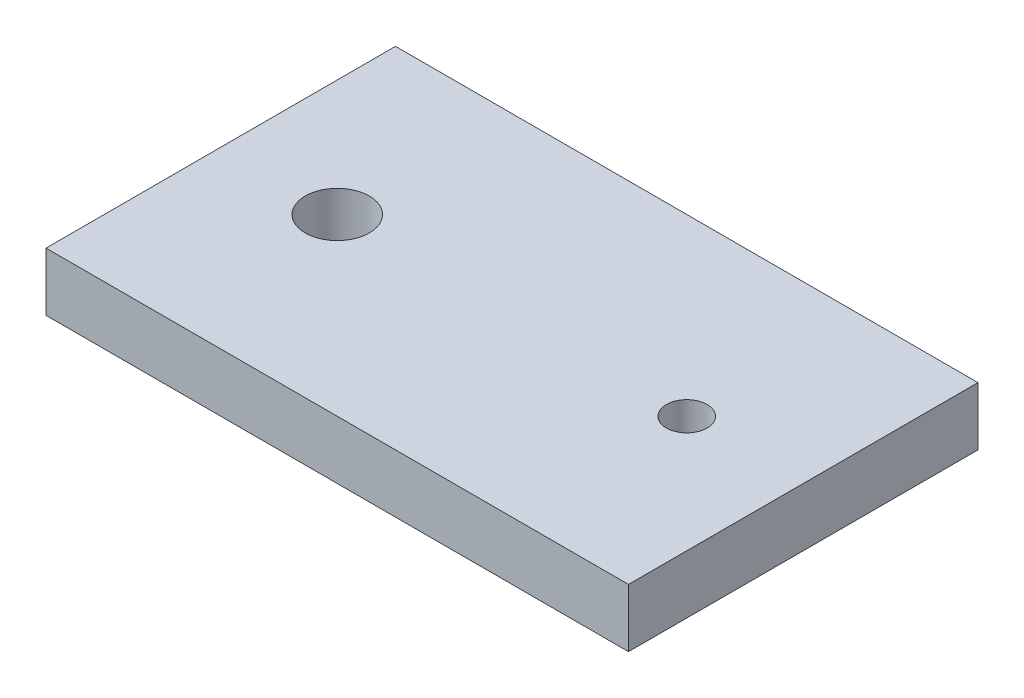
SolidWorks part; units mm, degrees
ref_plane "前视基准面" through (0, 0, 0) normal (0, 0, 1) x (1, 0, 0)
ref_plane "上视基准面" through (0, 0, 0) normal (0, 1, 0) x (1, 0, 0)
ref_plane "右视基准面" through (0, 0, 0) normal (1, 0, 0) x (0, 0, -1)
sketch "草图1" plane through (0, 0, 0) normal (0, 1, 0) x (1, 0, 0)
  line L0 (-24.1313, -2.1139) -> (25.8687, -2.1139) construction
  line L1 (-24.1313, 12.8861) -> (25.8687, 12.8861)
  line L2 (-24.1313, 12.8861) -> (-24.1313, -17.1139)
  line L3 (-24.1313, -17.1139) -> (25.8687, -17.1139)
  line L4 (25.8687, 12.8861) -> (25.8687, -17.1139)
  line L5 (-24.1313, 12.8861) -> (25.8687, -17.1139) construction
  line L6 (-24.1313, -17.1139) -> (25.8687, 12.8861) construction
  circle A0 centre (-14.1313, -2.1139) radius 2.75
  circle A1 centre (15.8687, -2.1139) radius 1.75
  point P4 (0.8687, -2.1139)
  dimension "D3" = 5.5
  dimension "D4" = 3.5
  dimension "D1" = 50
  dimension "D2" = 30
  dimension "D5" = 10
  dimension "D6" = 10
extrude "凸台-拉伸1" add sketch "草图1" along normal blind 5
